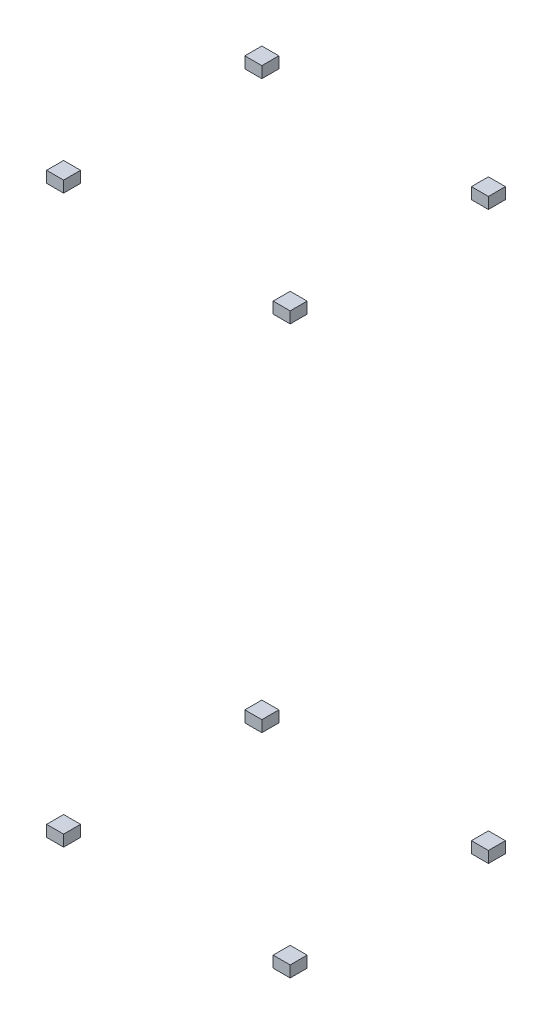
SolidWorks part; units mm, degrees
ref_plane "Front Plane" through (0, 0, 0) normal (0, 0, 1) x (1, 0, 0)
ref_plane "Top Plane" through (0, 0, 0) normal (0, 1, 0) x (1, 0, 0)
ref_plane "Right Plane" through (0, 0, 0) normal (1, 0, 0) x (0, 0, -1)
sketch "Sketch1" plane through (0, 0, 0) normal (0, 0, 1) x (1, 0, 0)
  line L1 (-860, -2040) -> (-740, -2040)
  line L2 (-860, -2040) -> (-860, -1960)
  line L3 (-860, -1960) -> (-740, -1960)
  line L4 (-740, -2040) -> (-740, -1960)
extrude "Boss-Extrude1" add sketch "Sketch1" along normal blind 120 from offset 760
sketch "Sketch2" plane through (0, 0, 0) normal (0, 0, 1) x (1, 0, 0)
  line L1 (-860, -2040) -> (-740, -2040)
  line L2 (-860, -2040) -> (-860, -1960)
  line L3 (-860, -1960) -> (-740, -1960)
  line L4 (-740, -2040) -> (-740, -1960)
extrude "Boss-Extrude2" add sketch "Sketch2" along normal blind 120 from offset 640
sketch "Sketch3" plane through (0, 0, 0) normal (0, 0, 1) x (1, 0, 0)
  line L1 (-860, 1960) -> (-740, 1960)
  line L2 (-860, 1960) -> (-860, 2040)
  line L3 (-860, 2040) -> (-740, 2040)
  line L4 (-740, 1960) -> (-740, 2040)
extrude "Boss-Extrude3" add sketch "Sketch3" along normal blind 120 from offset 760
sketch "Sketch4" plane through (0, 0, 0) normal (0, 0, 1) x (1, 0, 0)
  line L1 (-860, 1960) -> (-740, 1960)
  line L2 (-860, 1960) -> (-860, 2040)
  line L3 (-860, 2040) -> (-740, 2040)
  line L4 (-740, 1960) -> (-740, 2040)
extrude "Boss-Extrude4" add sketch "Sketch4" along normal blind 120 from offset 640
sketch "Sketch5" plane through (0, 0, 0) normal (0, 0, 1) x (1, 0, 0)
  line L1 (740, -2040) -> (860, -2040)
  line L2 (740, -2040) -> (740, -1960)
  line L3 (740, -1960) -> (860, -1960)
  line L4 (860, -2040) -> (860, -1960)
extrude "Boss-Extrude5" add sketch "Sketch5" along normal blind 120 from offset 760
sketch "Sketch6" plane through (0, 0, 0) normal (0, 0, 1) x (1, 0, 0)
  line L1 (740, -2040) -> (860, -2040)
  line L2 (740, -2040) -> (740, -1960)
  line L3 (740, -1960) -> (860, -1960)
  line L4 (860, -2040) -> (860, -1960)
extrude "Boss-Extrude6" add sketch "Sketch6" along normal blind 120 from offset 640
sketch "Sketch7" plane through (0, 0, 0) normal (0, 0, 1) x (1, 0, 0)
  line L1 (740, 1960) -> (860, 1960)
  line L2 (740, 1960) -> (740, 2040)
  line L3 (740, 2040) -> (860, 2040)
  line L4 (860, 1960) -> (860, 2040)
extrude "Boss-Extrude7" add sketch "Sketch7" along normal blind 120 from offset 760
sketch "Sketch8" plane through (0, 0, 0) normal (0, 0, 1) x (1, 0, 0)
  line L1 (740, 1960) -> (860, 1960)
  line L2 (740, 1960) -> (740, 2040)
  line L3 (740, 2040) -> (860, 2040)
  line L4 (860, 1960) -> (860, 2040)
extrude "Boss-Extrude8" add sketch "Sketch8" along normal blind 120 from offset 640
